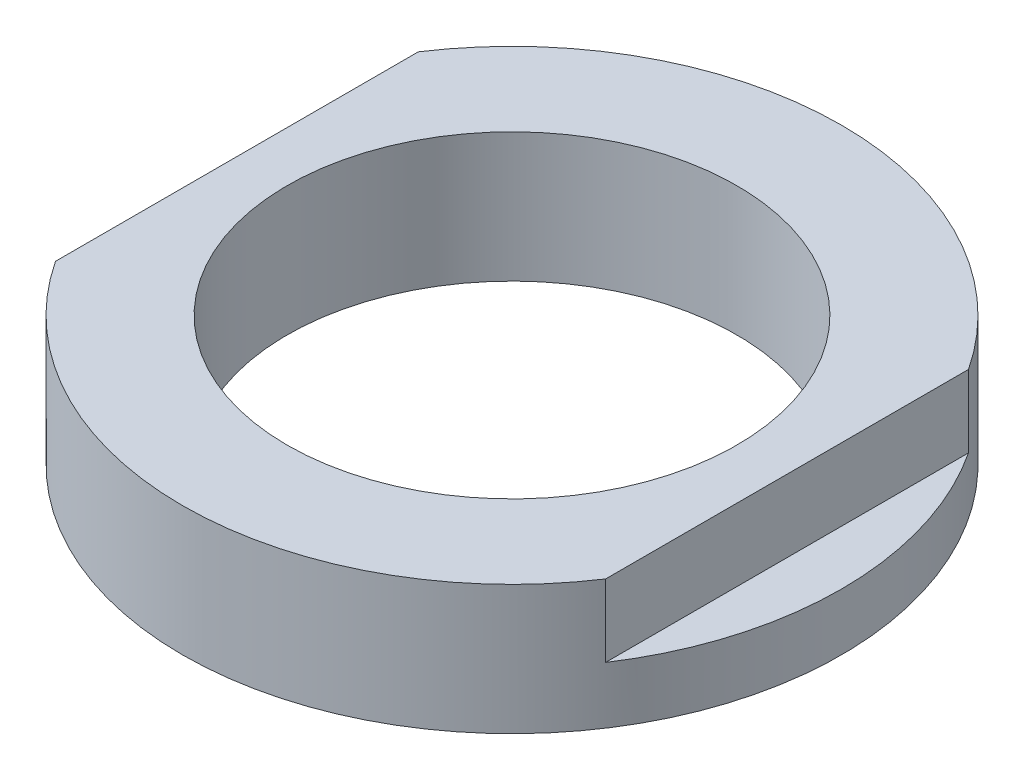
SolidWorks part; units mm, degrees
material "AISI 1035 Steel (SS)"
ref_plane "Front Plane" through (0, 0, 0) normal (0, 0, 1) x (1, 0, 0)
ref_plane "Top Plane" through (0, 0, 0) normal (0, 1, 0) x (1, 0, 0)
ref_plane "Right Plane" through (0, 0, 0) normal (1, 0, 0) x (0, 0, -1)
sketch "Sketch1" plane through (0, 0, 0) normal (0, 1, 0) x (1, 0, 0)
  circle A0 centre (0, 0) radius 14.24
  circle A1 centre (0, 0) radius 9.7155
  dimension "D1" = 28.48
  dimension "D2" = 19.431
extrude "Boss-Extrude1" add sketch "Sketch1" along normal mid plane 5.588
sketch "Sketch2" plane through (0, 2.794, 0) normal (0, 1, 0) x (1, 0, 0)
  line L0 (0, 0) -> (11.8872, 0) construction
  line L1 (11.8872, 10.5353) -> (16.4397, 10.5353)
  line L2 (11.8872, 10.5353) -> (11.8872, -10.5353)
  line L3 (11.8872, -10.5353) -> (16.4397, -10.5353)
  line L4 (16.4397, 10.5353) -> (16.4397, -10.5353)
  line L5 (0, 0) -> (0, 50000) construction
  dimension "D1" = 23.7744
  dimension "D2" = 4.5525
  dimension "D3" = 21.0705
extrude "Cut-Extrude1" cut sketch "Sketch2" against normal blind 3.1242
mirror "Mirror1" about plane through (0, 0, 0) normal (1, 0, 0) of "Cut-Extrude1"
sketch "Sketch3" plane through (0, 0, 0) normal (1, 0, 0) x (0, 0, -1)
  line L0 (-14.24, -2.794) -> (14.24, -2.794) construction
  line L1 (0, 0) -> (0, 50000) construction
  circle A0 centre (-12.208, -2.794) radius 0.7557
  dimension "D1" = 1.5113
  dimension "D2" = 2.032
revolve "Revolve1" add sketch "Sketch3" angle 360 about L1
